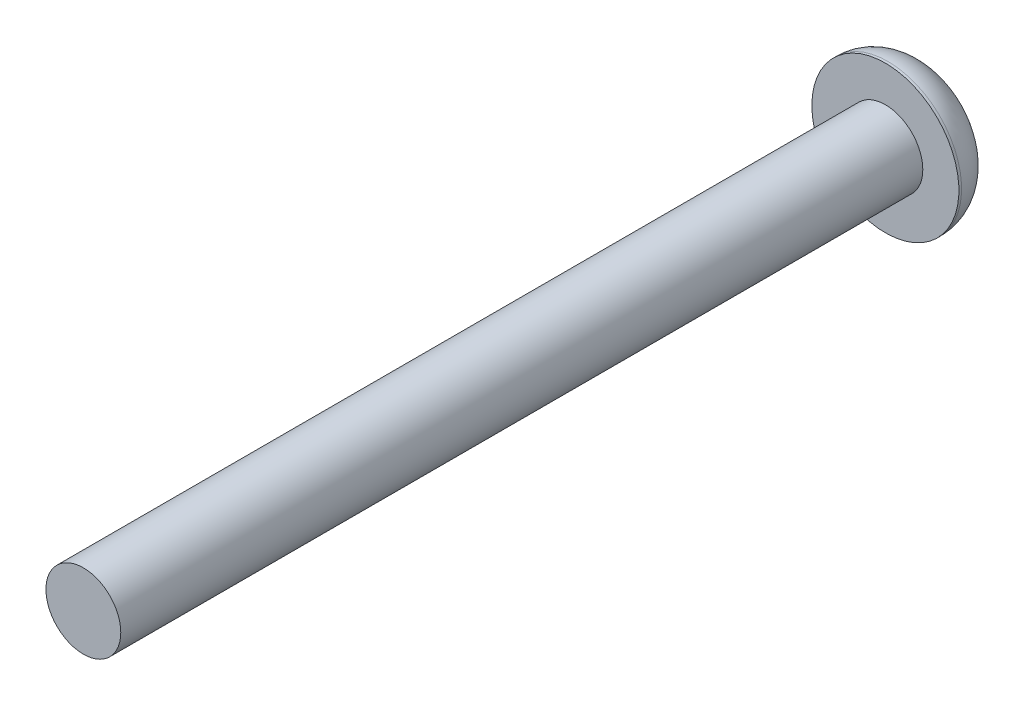
SolidWorks part; units mm, degrees
ref_plane "Front Plane" through (0, 0, 0) normal (0, 0, 1) x (1, 0, 0)
ref_plane "Top Plane" through (0, 0, 0) normal (0, 1, 0) x (1, 0, 0)
ref_plane "Right Plane" through (0, 0, 0) normal (1, 0, 0) x (0, 0, -1)
sketch "Sketch1" plane through (0, 0, 0) normal (0, 0, 1) x (1, 0, 0)
  circle A0 centre (0, 0) radius 1.4
  dimension "D1" = 2.8
extrude "Boss-Extrude1" add sketch "Sketch1" along normal blind 30
sketch "Sketch2" plane through (0, 0, 0) normal (0, 0, -1) x (-1, 0, 0)
  circle A0 centre (0, 0) radius 2.75
  dimension "D1" = 5.5
extrude "Boss-Extrude2" add sketch "Sketch2" along normal blind 1.6
fillet "Fillet1" radius 1.5 1 edges at (-2.75, 0, -1.6)
